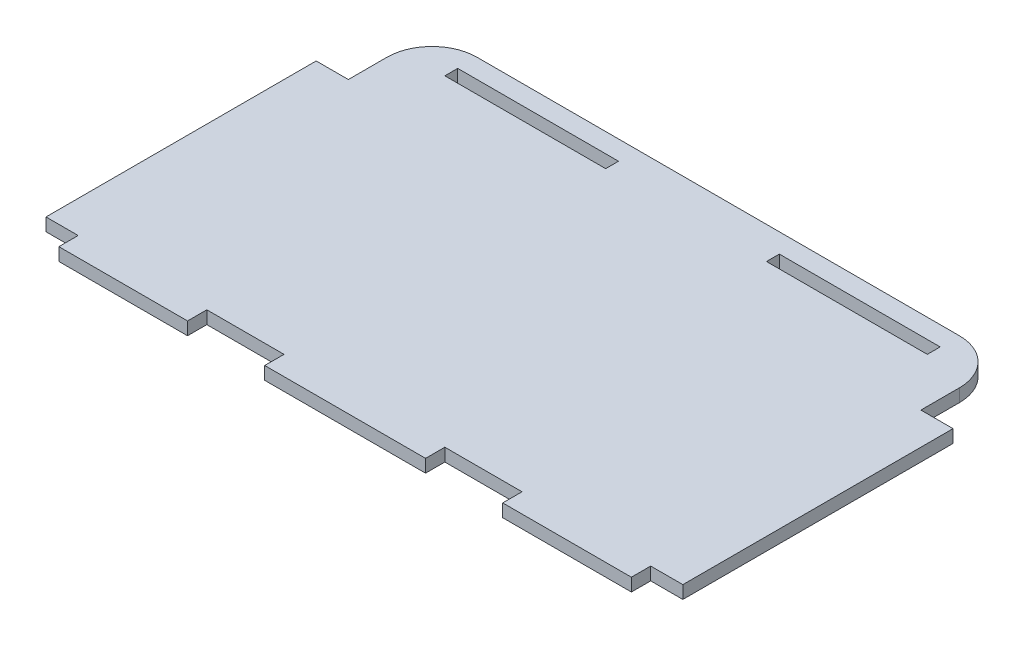
SolidWorks part; units mm, degrees
material "PVC rigido"
ref_plane "Piano frontale" through (0, 0, 0) normal (0, 0, 1) x (1, 0, 0)
ref_plane "Piano superiore" through (0, 0, 0) normal (0, 1, 0) x (1, 0, 0)
ref_plane "Piano destro" through (0, 0, 0) normal (1, 0, 0) x (0, 0, -1)
sketch "Schizzo1" plane through (0, 0, 0) normal (0, 0, 1) x (1, 0, 0)
  line L1 (-44.5, -23.5) -> (44.5, -23.5)
  line L2 (-44.5, -23.5) -> (-44.5, -21.5)
  line L3 (-44.5, -21.5) -> (44.5, -21.5)
  line L4 (44.5, -23.5) -> (44.5, -21.5)
extrude "Estrusione-Estrusione1" add sketch "Schizzo1" along normal up to surface (45 mm away) and the other way up to surface (3 mm away)
sketch "Schizzo2" plane through (0, -21.5, 0) normal (0, 1, 0) x (1, 0, 0)
  line L0 (-44.5, -45) -> (44.5, -45) construction
  line L1 (24.5, -45) -> (12.5, -45)
  line L2 (24.5, -45) -> (24.5, -42)
  line L3 (24.5, -42) -> (12.5, -42)
  line L4 (12.5, -45) -> (12.5, -42)
  line L5 (24.5, -45) -> (24.5, -42) construction
  line L6 (-12.5, -45) -> (-24.5, -45)
  line L7 (-12.5, -45) -> (-12.5, -42)
  line L8 (-12.5, -42) -> (-24.5, -42)
  line L9 (-24.5, -45) -> (-24.5, -42)
  line L10 (12.5, -45) -> (12.5, -42) construction
  line L11 (-24.5, -45) -> (-24.5, -42) construction
extrude "Taglio-Estrusione1" cut sketch "Schizzo2" against normal blind 10
ref_plane "Piano1" through (0, 0, 0) normal (1, 0, 0) x (0, 0, -1)
sketch "Schizzo3" plane through (44.5, 0, 0) normal (1, 0, 0) x (0, 0, -1)
  line L0 (-45, -23.5) -> (3, -23.5) construction
  line L1 (0, -21.5) -> (-42, -21.5)
  line L2 (0, -21.5) -> (0, -23.5)
  line L3 (0, -23.5) -> (-42, -23.5)
  line L4 (-42, -21.5) -> (-42, -23.5)
  line L5 (-42, -21.5) -> (-42, -23.5) construction
extrude "Estrusione-Estrusione2" add sketch "Schizzo3" along normal blind 5
mirror "Specchia1" about plane through (0, 0, 0) normal (1, 0, 0) of "Estrusione-Estrusione2"
sketch "Schizzo4" plane through (0, 0, -3) normal (0, 0, -1) x (-1, 0, 0)
  line L1 (44.5, -21.5) -> (-44.5, -21.5)
  line L2 (44.5, -21.5) -> (44.5, -23.5)
  line L3 (44.5, -23.5) -> (-44.5, -23.5)
  line L4 (-44.5, -21.5) -> (-44.5, -23.5)
extrude "Estrusione-Estrusione3" add sketch "Schizzo4" along normal blind 10
sketch "Schizzo5" plane through (0, -21.5, 0) normal (0, 1, 0) x (1, 0, 0)
  line L0 (-12.5, 9) -> (12.5, 9) construction
  line L1 (-37.5, 10) -> (-12.5, 10)
  line L2 (-37.5, 10) -> (-37.5, 8)
  line L3 (-37.5, 8) -> (-12.5, 8)
  line L4 (-12.5, 10) -> (-12.5, 8)
  line L5 (12.5, 10) -> (37.5, 10)
  line L6 (12.5, 10) -> (12.5, 8)
  line L7 (12.5, 8) -> (37.5, 8)
  line L8 (37.5, 10) -> (37.5, 8)
  line L9 (0, 9) -> (0, 13) construction
  line L10 (-44.5, 13) -> (44.5, 13) construction
  line L11 (-37.5, 9) -> (-44.5, 9) construction
  line L12 (-44.5, 0) -> (-44.5, 13) construction
  line L13 (37.5, 9) -> (44.5, 9) construction
  line L14 (44.5, 0) -> (44.5, 13) construction
  dimension "D1" = 2
  dimension "D2" = 4
  dimension "D3" = 25
  dimension "D4" = 25
extrude "Taglio-Estrusione2" cut sketch "Schizzo5" against normal blind 8
fillet "Raccordo1" radius 7 2 edges at (-44.5, -22.5, -13) (44.5, -22.5, -13)
